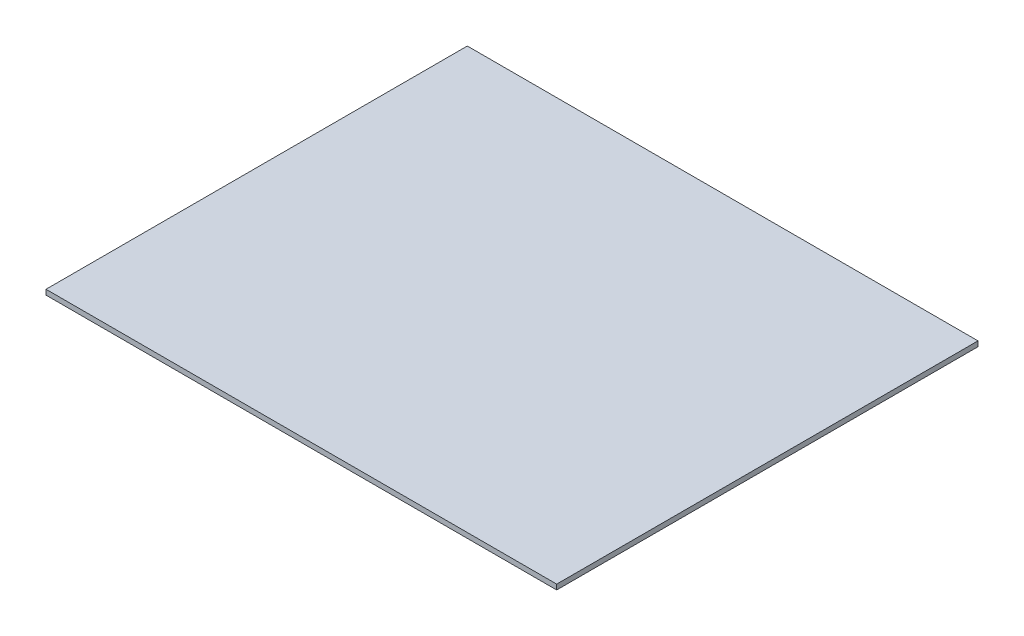
SolidWorks part; units mm, degrees
ref_plane "Ön Düzlem" through (0, 0, 0) normal (0, 0, 1) x (1, 0, 0)
ref_plane "Üst Düzlem" through (0, 0, 0) normal (0, 1, 0) x (1, 0, 0)
ref_plane "Sağ Düzlem" through (0, 0, 0) normal (1, 0, 0) x (0, 0, -1)
sketch "Çizim1" plane through (0, 0, 0) normal (0, 1, 0) x (1, 0, 0)
  line L1 (200, 165) -> (-200, 165)
  line L2 (200, 165) -> (200, -165)
  line L3 (200, -165) -> (-200, -165)
  line L4 (-200, 165) -> (-200, -165)
  line L5 (200, 165) -> (-200, -165) construction
  line L6 (200, -165) -> (-200, 165) construction
  point P0 (0, 0)
  dimension "D1" = 330
  dimension "D2" = 400
extrude "Yükseklik-Ekstrüzyon1" add sketch "Çizim1" along normal blind 4
